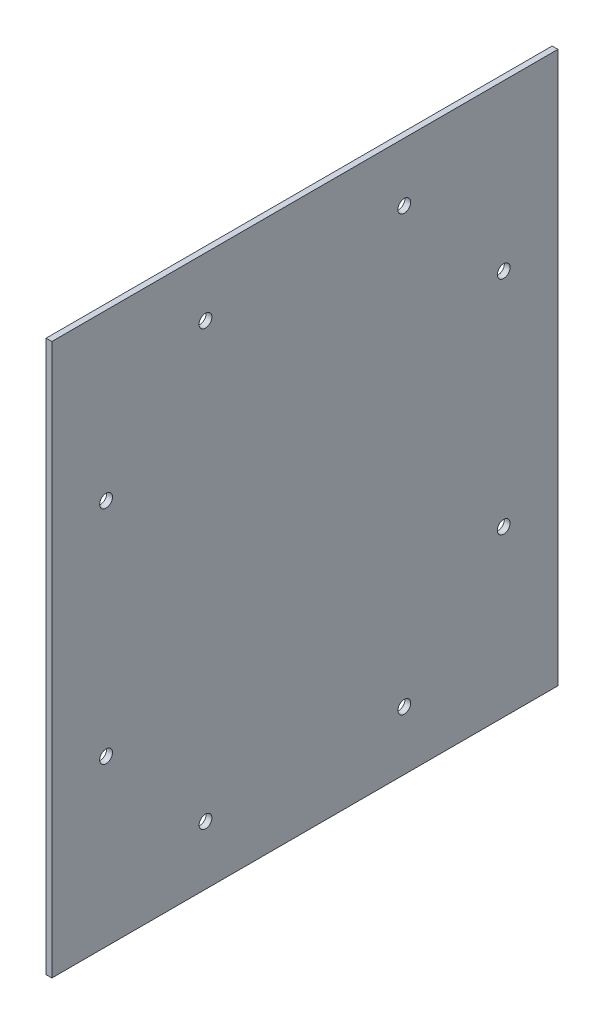
SolidWorks part; units mm, degrees
material "6061-T6 (SS)"
ref_plane "X-Y Datum" through (0, 0, 0) normal (0, 0, 1) x (1, 0, 0)
ref_plane "X-Z Datum" through (0, 0, 0) normal (0, 1, 0) x (1, 0, 0)
ref_plane "Y-Z Datum" through (0, 0, 0) normal (1, 0, 0) x (0, 0, -1)
sketch "Sketch1" plane through (0, 0, 0) normal (1, 0, 0) x (0, 0, -1)
  line L0 (69.85, -152.4) -> (-69.85, -152.4) construction
  line L1 (-177.8, -193.675) -> (177.8, -193.675)
  line L2 (-177.8, -193.675) -> (-177.8, 193.675)
  line L3 (-177.8, 193.675) -> (177.8, 193.675)
  line L4 (177.8, -193.675) -> (177.8, 193.675)
  line L5 (-177.8, -193.675) -> (177.8, 193.675) construction
  line L6 (-177.8, 193.675) -> (177.8, -193.675) construction
  line L7 (-139.7, -77.7875) -> (-139.7, 77.7875) construction
  line L8 (-69.85, -152.4) -> (-139.7, -77.7875) construction
  line L9 (55, 0) -> (-55, 0) construction
  line L10 (0, 55) -> (0, -55) construction
  line L11 (69.85, -152.4) -> (139.7, -77.7875) construction
  line L12 (139.7, -77.7875) -> (139.7, 77.7875) construction
  line L13 (139.7, 77.7875) -> (69.85, 152.4) construction
  line L14 (69.85, 152.4) -> (-69.85, 152.4) construction
  line L15 (-69.85, 152.4) -> (-139.7, 77.7875) construction
  circle A0 centre (69.85, -152.4) radius 4.0005
  circle A1 centre (-69.85, -152.4) radius 4.0005
  circle A2 centre (-139.7, -77.7875) radius 4.0005
  circle A3 centre (-139.7, 77.7875) radius 4.0005
  circle A4 centre (69.85, 152.4) radius 4.0005
  circle A5 centre (-69.85, 152.4) radius 4.0005
  circle A6 centre (139.7, 77.7875) radius 4.0005
  circle A7 centre (139.7, -77.7875) radius 4.0005
  point P0 (0, 0)
  point P10 (0, -152.4)
  point P15 (-139.7, 0)
  dimension "D4" = 8.001
  dimension "D1" = 387.35
  dimension "D2" = 355.6
  dimension "D3" = 41.275
  dimension "D5" = 139.7
  dimension "D6" = 155.575
  dimension "D7" = 38.1
  dimension "D8" = 102.2059
extrude "Boss-Extrude1" add sketch "Sketch1" along normal blind 4.064 contours L1 L4 L3 L2 A6 A4 A3 A2 A1 A0 A5 A7 | A1 | A0 | A7 | A6 | A4 | A5 | A3 | A2
hole_wizard "M8 Clearance Hole1" positions "Sketch2" profile "Sketch3" hole size "M8" standard "ANSI Metric" end condition through all
sketch "Sketch2" plane through (4.064, 0, 0) normal (1, 0, 0) x (0, 0, -1)
  point P0 (-139.7, 77.7875)
  point P3 (-69.85, 152.4)
  point P6 (69.85, 152.4)
  point P9 (139.7, 77.7875)
  point P12 (139.7, -77.7875)
  point P15 (69.85, -152.4)
  point P18 (-69.85, -152.4)
  point P21 (-139.7, -77.7875)
sketch "Sketch3" plane through (4.064, 77.7875, 139.7) normal (0, 1, 0) x (0, 0, -1)
  line L0 (0, 0) -> (0, 4.064)
  line L1 (0, 4.064) -> (4.5, 4.064)
  line L2 (4.5, 4.064) -> (4.5, 0)
  line L5 (4.5, 0) -> (0, 0)
  line L11 (0, -6.35) -> (0, 107.95) construction
  dimension "Thru Hole Dia." = 9
  dimension "Thru Hole Depth" = 4.064
